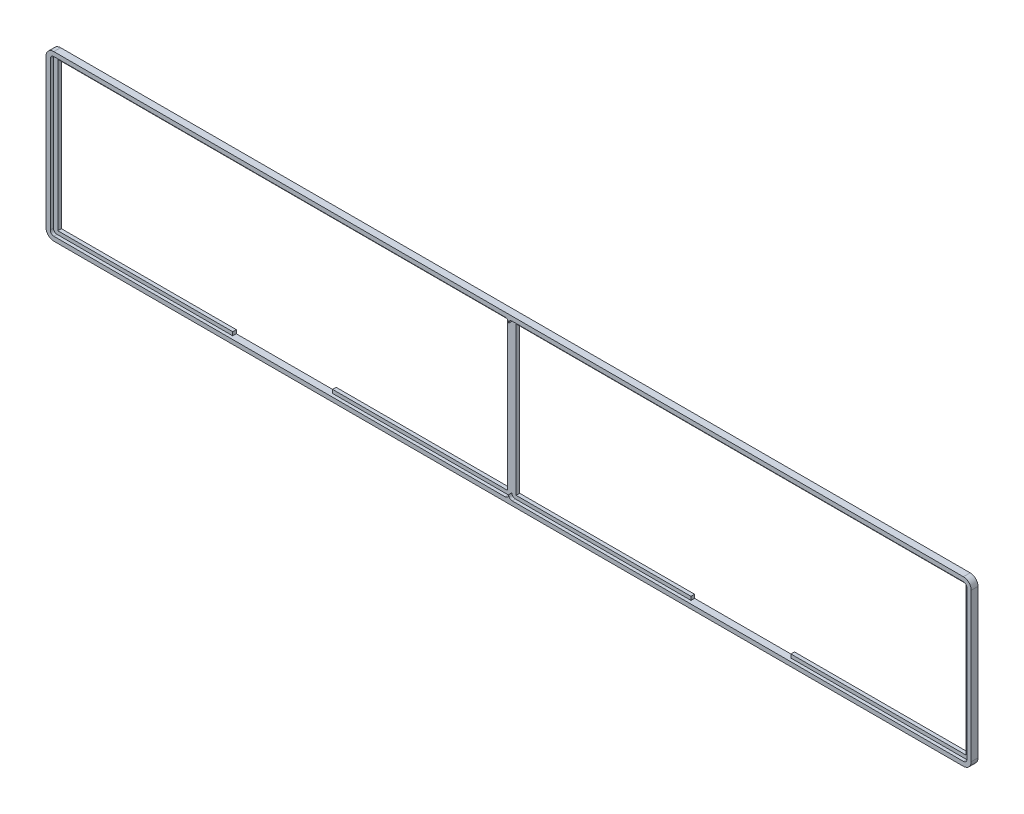
SolidWorks part; units mm, degrees
ref_plane "Front Plane" through (0, 0, 0) normal (0, 0, 1) x (1, 0, 0)
ref_plane "Top Plane" through (0, 0, 0) normal (0, 1, 0) x (1, 0, 0)
ref_plane "Right Plane" through (0, 0, 0) normal (1, 0, 0) x (0, 0, -1)
sketch "Sketch1" plane through (0, 0, 30) normal (0, 0, 1) x (1, 0, 0)
  line L0 (-291, 3.75) -> (-291, -100.25)
  line L1 (-285.5, -105.75) -> (30.5, -105.75)
  line L2 (35.5, -105.75) -> (351.5, -105.75)
  line L3 (357, -100.25) -> (357, 3.75)
  line L4 (33, -100.25) -> (33, 3.75)
  line L5 (30.5, 6.25) -> (-285.5, 6.25)
  line L6 (-288, 3.75) -> (-288, -100.25)
  line L7 (-285.5, -102.75) -> (30.5, -102.75)
  line L9 (30.5, 6.25) -> (-285.5, 6.25)
  line L10 (-288, 3.75) -> (-288, -100.25)
  line L11 (-285.5, -102.75) -> (30.5, -102.75)
  line L12 (354, -100.25) -> (354, 3.75)
  line L13 (351.5, 6.25) -> (35.5, 6.25)
  line L14 (33, 3.75) -> (33, -100.25)
  line L15 (35.5, -102.75) -> (351.5, -102.75)
  line L16 (354, -100.25) -> (354, 3.75)
  line L17 (351.5, 6.25) -> (35.5, 6.25)
  line L19 (35.5, -102.75) -> (351.5, -102.75)
  line L20 (351.5, 9.25) -> (35.5, 9.25)
  line L21 (30.5, 9.25) -> (-285.5, 9.25)
  line L22 (30.5, -105.75) -> (35.5, -105.75)
  line L23 (30.5, 9.25) -> (35.5, 9.25)
  arc A0 (-285.5, 9.25) -> (-291, 3.75) centre (-285.5, 3.75) ccw
  arc A1 (-291, -100.25) -> (-285.5, -105.75) centre (-285.5, -100.25) ccw
  arc A4 (30.5, -102.75) -> (33, -100.25) centre (30.5, -100.25) ccw
  arc A5 (33, 3.75) -> (30.5, 6.25) centre (30.5, 3.75) ccw
  arc A6 (-285.5, 6.25) -> (-288, 3.75) centre (-285.5, 3.75) ccw
  arc A7 (-288, -100.25) -> (-285.5, -102.75) centre (-285.5, -100.25) ccw
  arc A8 (30.5, -102.75) -> (33, -100.25) centre (30.5, -100.25) ccw
  arc A9 (33, 3.75) -> (30.5, 6.25) centre (30.5, 3.75) ccw
  arc A10 (-285.5, 6.25) -> (-288, 3.75) centre (-285.5, 3.75) ccw
  arc A11 (-288, -100.25) -> (-285.5, -102.75) centre (-285.5, -100.25) ccw
  arc A12 (351.5, -102.75) -> (354, -100.25) centre (351.5, -100.25) ccw
  arc A13 (354, 3.75) -> (351.5, 6.25) centre (351.5, 3.75) ccw
  arc A14 (35.5, 6.25) -> (33, 3.75) centre (35.5, 3.75) ccw
  arc A15 (33, -100.25) -> (35.5, -102.75) centre (35.5, -100.25) ccw
  arc A16 (351.5, -102.75) -> (354, -100.25) centre (351.5, -100.25) ccw
  arc A17 (354, 3.75) -> (351.5, 6.25) centre (351.5, 3.75) ccw
  arc A18 (35.5, 6.25) -> (33, 3.75) centre (35.5, 3.75) ccw
  arc A19 (33, -100.25) -> (35.5, -102.75) centre (35.5, -100.25) ccw
  arc A20 (351.5, -105.75) -> (357, -100.25) centre (351.5, -100.25) ccw
  arc A21 (357, 3.75) -> (351.5, 9.25) centre (351.5, 3.75) ccw
  arc A24 (33, 8.649) -> (30.5, 9.25) centre (30.5, 3.75) ccw construction
  arc A25 (35.5, 9.25) -> (33, 8.649) centre (35.5, 3.75) ccw construction
  arc A26 (30.5, -105.75) -> (33, -105.149) centre (30.5, -100.25) ccw construction
  arc A27 (33, -105.149) -> (35.5, -105.75) centre (35.5, -100.25) ccw construction
  dimension "D1" = 0
  dimension "D2" = 0
  dimension "D3" = 3
extrude "Boss-Extrude1" add sketch "Sketch1" against normal blind 2.25
sketch "Sketch2" plane through (0, 0, 27.75) normal (0, 0, -1) x (-1, 0, 0)
  line L0 (-36, 3.75) -> (-351, 3.75) construction
  line L1 (285, 3.75) -> (-30, 3.75) construction
  line L2 (285, -100.25) -> (285, 3.75) construction
  line L3 (162.5, -102.75) -> (162.5, -100.25) construction
  line L4 (285.5, 9.25) -> (-351.5, 9.25)
  line L5 (-357, 3.75) -> (-357, -100.25)
  line L6 (-351.5, -105.75) -> (285.5, -105.75)
  line L7 (291, -100.25) -> (291, 3.75)
  line L8 (285.5, 9.25) -> (-351.5, 9.25)
  line L9 (-357, 3.75) -> (-357, -100.25)
  line L10 (-351.5, -105.75) -> (285.5, -105.75)
  line L11 (291, -100.25) -> (291, 3.75)
  line L12 (162.5, -100.25) -> (285, -100.25) construction
  line L13 (92.5, -100.25) -> (92.5, -102.75) construction
  line L14 (-30, -100.25) -> (92.5, -100.25) construction
  line L15 (-30, 3.75) -> (-30, -100.25) construction
  line L16 (-36, -100.25) -> (-36, 3.75) construction
  line L17 (-158.5, -100.25) -> (-36, -100.25) construction
  line L18 (-158.5, -102.75) -> (-158.5, -100.25) construction
  line L19 (-228.5, -100.25) -> (-228.5, -102.75) construction
  line L20 (-351, -100.25) -> (-228.5, -100.25) construction
  line L21 (-351, 3.75) -> (-351, -100.25) construction
  line L22 (-36, 3.75) -> (-351, 3.75)
  line L23 (285, 3.75) -> (-30, 3.75)
  line L24 (285, -100.25) -> (285, 3.75)
  line L25 (162.5, -102.75) -> (162.5, -100.25)
  line L26 (162.5, -100.25) -> (285, -100.25)
  line L27 (92.5, -100.25) -> (92.5, -102.75)
  line L28 (-30, -100.25) -> (92.5, -100.25)
  line L29 (-30, 3.75) -> (-30, -100.25)
  line L30 (-36, -100.25) -> (-36, 3.75)
  line L31 (-158.5, -100.25) -> (-36, -100.25)
  line L32 (-158.5, -102.75) -> (-158.5, -100.25)
  line L33 (-228.5, -100.25) -> (-228.5, -102.75)
  line L34 (-351, -100.25) -> (-228.5, -100.25)
  line L35 (-351, 3.75) -> (-351, -100.25)
  arc A4 (291, 3.75) -> (285.5, 9.25) centre (285.5, 3.75) ccw
  arc A5 (-351.5, 9.25) -> (-357, 3.75) centre (-351.5, 3.75) ccw
  arc A6 (-357, -100.25) -> (-351.5, -105.75) centre (-351.5, -100.25) ccw
  arc A7 (285.5, -105.75) -> (291, -100.25) centre (285.5, -100.25) ccw
  arc A8 (291, 3.75) -> (285.5, 9.25) centre (285.5, 3.75) ccw
  arc A9 (-351.5, 9.25) -> (-357, 3.75) centre (-351.5, 3.75) ccw
  arc A10 (-357, -100.25) -> (-351.5, -105.75) centre (-351.5, -100.25) ccw
  arc A11 (285.5, -105.75) -> (291, -100.25) centre (285.5, -100.25) ccw
  line M9 (285.5, -102.75) -> (-30.5, -102.75)
  arc M10 (-30.5, -102.75) -> (-33, -100.25) centre (-30.5, -100.25) cw
  arc M11 (-33, -100.25) -> (-35.5, -102.75) centre (-35.5, -100.25) cw
  line M12 (-35.5, -102.75) -> (-351.5, -102.75)
  arc M13 (-351.5, -102.75) -> (-354, -100.25) centre (-351.5, -100.25) cw
  line M14 (-354, -100.25) -> (-354, 3.75)
  arc M15 (-354, 3.75) -> (-351.5, 6.25) centre (-351.5, 3.75) cw
  line M16 (-351.5, 6.25) -> (-35.5, 6.25)
  arc M17 (-35.5, 6.25) -> (-33, 3.75) centre (-35.5, 3.75) cw
  arc M18 (-33, 3.75) -> (-30.5, 6.25) centre (-30.5, 3.75) cw
  line M19 (-30.5, 6.25) -> (285.5, 6.25)
  arc M20 (285.5, 6.25) -> (288, 3.75) centre (285.5, 3.75) cw
  line M21 (288, 3.75) -> (288, -100.25)
  arc M22 (288, -100.25) -> (285.5, -102.75) centre (285.5, -100.25) cw
  arc M23 (291, 3.75) -> (285.5, 9.25) centre (285.5, 3.75) ccw
  line M24 (285.5, 9.25) -> (-351.5, 9.25)
  arc M25 (-351.5, 9.25) -> (-357, 3.75) centre (-351.5, 3.75) ccw
  line M26 (-357, 3.75) -> (-357, -100.25)
  arc M27 (-357, -100.25) -> (-351.5, -105.75) centre (-351.5, -100.25) ccw
  line M28 (-351.5, -105.75) -> (285.5, -105.75)
  arc M29 (285.5, -105.75) -> (291, -100.25) centre (285.5, -100.25) ccw
  line M30 (291, -100.25) -> (291, 3.75)
  dimension "D1" = 0
extrude "Boss-Extrude2" add sketch "Sketch2" along normal blind 2.5 contours L35 L22 L30 L31 L32 L27 L28 L29 L23 L24 L26 L25 L33 L34 M12 M11 M10 M9 M22 M21 M20 M19 M18 M17 M16 M15 M14 M13 | M30 M23 M24 M25 M26 M27 M28 M29 M22 M9 M10 M11 M12 M13 M14 M15 M16 M17 M18 M19 M20 M21
